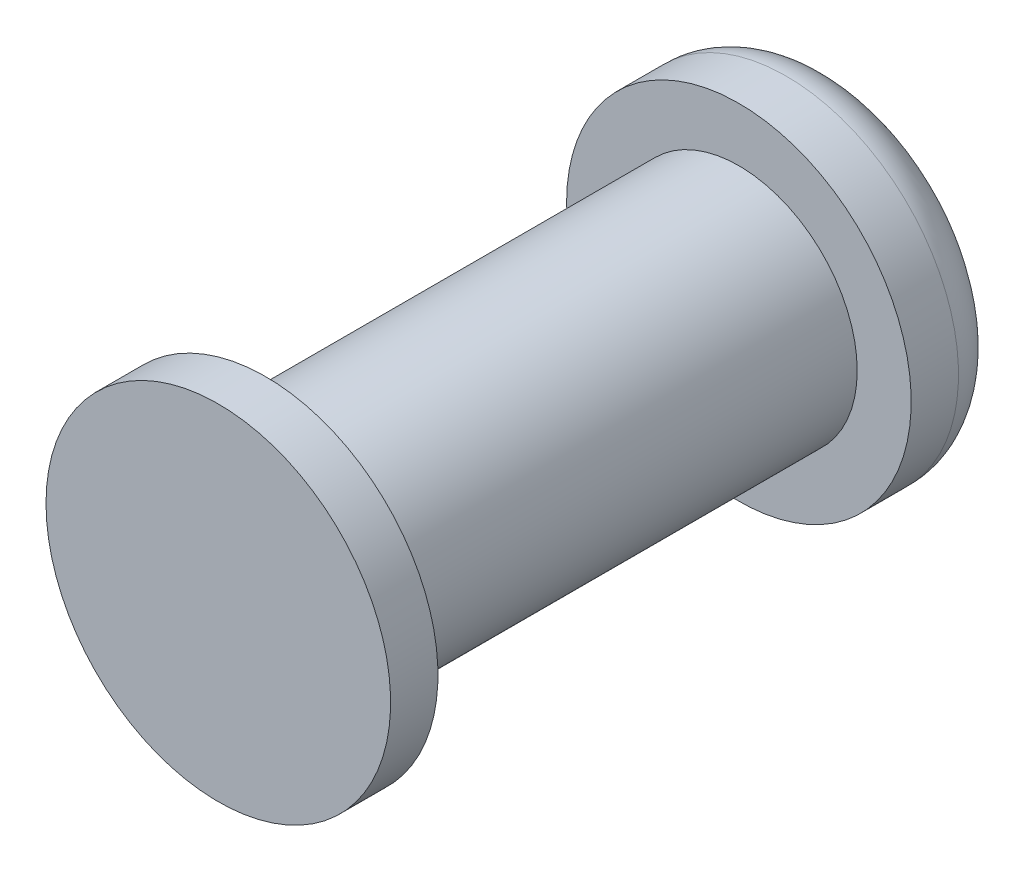
SolidWorks part; units mm, degrees
ref_plane "Front Plane" through (0, 0, 0) normal (0, 0, 1) x (1, 0, 0)
ref_plane "Top Plane" through (0, 0, 0) normal (0, 1, 0) x (1, 0, 0)
ref_plane "Right Plane" through (0, 0, 0) normal (1, 0, 0) x (0, 0, -1)
sketch "Sketch1" plane through (0, 0, 0) normal (0, 0, 1) x (1, 0, 0)
  circle A0 centre (0, 0) radius 0.635
  dimension "D1" = 1.27
extrude "Boss-Extrude1" add sketch "Sketch1" along normal blind 2.794
sketch "Sketch3" plane through (0, 0, 0) normal (0, 0, -1) x (-1, 0, 0)
  circle A0 centre (0, 0) radius 0.9248
  dimension "D1" = 1.8496
extrude "Boss-Extrude2" add sketch "Sketch3" along normal blind 0.508
fillet "Fillet2" radius 0.254 1 edges at (-0.9248, 0, -0.508)
sketch "Sketch4" plane through (0, 0, 0) normal (0, 1, 0) x (1, 0, 0)
  line L0 (0.635, -2.794) -> (0.9248, -2.794)
  line L1 (0.9248, -2.794) -> (0.9248, -2.54)
  line L2 (0.9248, -2.54) -> (0.635, -2.54)
  line L3 (0.635, -2.794) -> (0.635, 0) construction
  line L4 (0.9248, 0) -> (0.9248, -3.2756) construction
  line L5 (0.635, -2.794) -> (0.635, -2.54)
  line L6 (0.635, -2.54) -> (0.635, -2.794)
  dimension "D1" = 0.254
  dimension "D2" = 0
sketch "Sketch6" plane through (0, 0, 0) normal (0, 1, 0) x (1, 0, 0)
  line L0 (0, 1.1701) -> (0, -3.8459) construction
revolve "Revolve2" add sketch "Sketch4" angle 360 about L0
